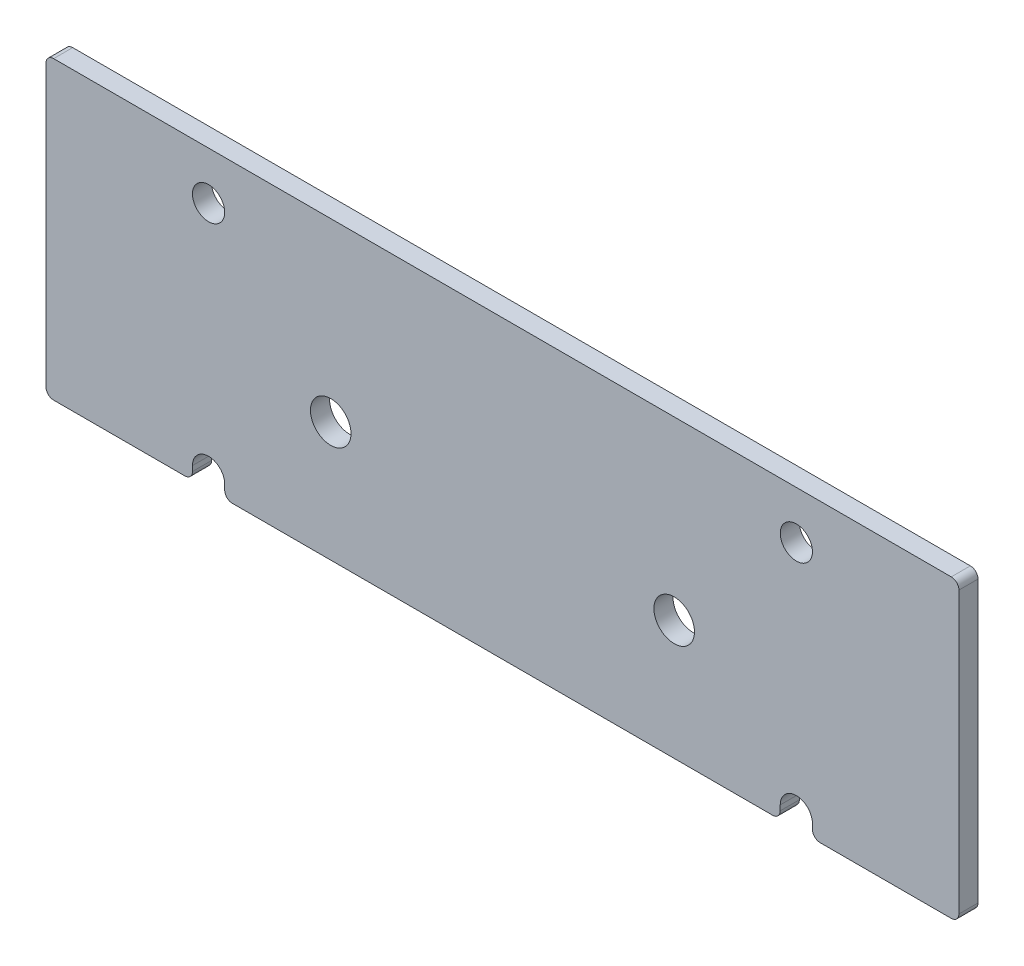
SolidWorks part; units mm, degrees
material "Plain Carbon Steel"
ref_plane "Front Plane" through (0, 0, 0) normal (0, 0, 1) x (1, 0, 0)
ref_plane "Top Plane" through (0, 0, 0) normal (0, 1, 0) x (1, 0, 0)
ref_plane "Right Plane" through (0, 0, 0) normal (1, 0, 0) x (0, 0, -1)
sketch "Sketch1" plane through (0, 0, 0) normal (0, 0, 1) x (1, 0, 0)
  line L0 (127, 0) -> (-127, 0) construction
  line L1 (101.6, -357.1875) -> (101.6, 357.1875) construction
  line L2 (152.4, 0) -> (152.4, 357.1875) construction
  line L3 (-101.6, -357.1875) -> (-101.6, 357.1875) construction
  line L4 (-152.4, -357.1875) -> (-152.4, 357.1875) construction
  line L5 (101.6, 59.0332) -> (-101.6, 262.2332) construction
  line L6 (101.6, 94.9543) -> (-101.6, 298.1543) construction
  line L7 (0, 196.5543) -> (0, 160.6332) construction
  line L8 (0, 178.5938) -> (152.4, 178.5938) construction
  line L9 (105.003, 12.7) -> (-105.003, 12.7) construction
  line L10 (105.003, -12.7) -> (-105.003, -12.7) construction
  line L11 (-101.6, 59.0332) -> (101.6, 262.2332) construction
  line L12 (-101.6, 94.9543) -> (101.6, 298.1543) construction
  line L13 (152.4, 0) -> (152.4, -357.1875) construction
  line L14 (-101.6, -94.9543) -> (101.6, -298.1543) construction
  line L15 (-101.6, -59.0332) -> (101.6, -262.2332) construction
  line L16 (101.6, -94.9543) -> (-101.6, -298.1543) construction
  line L17 (101.6, -59.0332) -> (-101.6, -262.2332) construction
  line L18 (-179.07, -25.4) -> (-179.07, 128.4583)
  line L19 (-179.07, 128.4583) -> (179.07, 128.4583)
  line L20 (179.07, 128.4583) -> (179.07, -25.4)
  line L21 (179.07, -25.4) -> (153.67, -25.4)
  line L22 (153.67, -25.4) -> (153.67, -1.27)
  line L23 (100.33, -1.27) -> (100.33, -25.4)
  line L24 (100.33, -25.4) -> (-100.33, -25.4)
  line L25 (-100.33, -25.4) -> (-100.33, -1.27)
  line L26 (-153.67, -1.27) -> (-153.67, -25.4)
  line L27 (-179.07, -25.4) -> (-153.67, -25.4)
  circle A0 centre (-127, 0) radius 25.4 construction
  circle A1 centre (127, 0) radius 25.4 construction
  circle A2 centre (-127, 357.1875) radius 25.4 construction
  circle A3 centre (127, 357.1875) radius 25.4 construction
  arc A4 (100.33, -1.27) -> (153.67, -1.27) centre (127, -1.27) cw
  arc A5 (-100.33, -1.27) -> (-153.67, -1.27) centre (-127, -1.27) ccw
  circle A6 centre (96.139, 108.1383) radius 5.461 construction
  point P23 (0, 178.5938)
  point P33 (101.6, 0)
  point P37 (-152.4, 0)
  point P38 (-101.6, 0)
  point P53 (127, 25.4)
  point P54 (127, 25.4)
  dimension "D2" = 50.8
  dimension "D7" = 26.67
  dimension "D9" = 25.4
  dimension "D10" = 10.922
  dimension "D1" = 254
  dimension "D3" = 357.1875
  dimension "D4" = 25.4
  dimension "D5" = 45
  dimension "D6" = 25.4
  dimension "D8" = 25.4
  dimension "D11" = 20.32
extrude "Boss-Extrude1" add sketch "Sketch1" along normal blind 6.35
sketch "Sketch9" plane through (0, 0, 6.35) normal (0, 0, 1) x (1, 0, 0)
  line L0 (-151.892, 128.4583) -> (-151.892, 8.3048)
  line L2 (-152.4, -357.1875) -> (-152.4, 357.1875) construction
  line L3 (179.07, 128.4583) -> (-179.07, 128.4583) construction
  line L4 (-151.892, 128.4583) -> (-179.07, 128.4583)
  line L5 (-179.07, 128.4583) -> (-179.07, -25.4)
  line L6 (-179.07, -25.4) -> (-153.67, -25.4)
  line L7 (-179.07, -25.4) -> (-153.67, -25.4) construction
  line L8 (-153.67, -25.4) -> (-153.67, -1.27) construction
  line L9 (-153.67, -25.4) -> (-153.67, -1.27)
  line L10 (0, 0) -> (0, 128.4583) construction
  line L11 (153.67, -25.4) -> (153.67, -1.27)
  line L12 (179.07, -25.4) -> (153.67, -25.4)
  line L13 (179.07, 128.4583) -> (179.07, -25.4)
  line L14 (151.892, 128.4583) -> (179.07, 128.4583)
  line L15 (151.892, 128.4583) -> (151.892, 8.3048)
  arc A0 (-100.33, -1.27) -> (-153.67, -1.27) centre (-127, -1.27) ccw construction
  arc A1 (-153.67, -1.27) -> (-151.892, 8.3048) centre (-127, -1.27) cw
  arc A2 (153.67, -1.27) -> (151.892, 8.3048) centre (127, -1.27) ccw
  dimension "D1" = 0.508
extrude "Cut-Extrude3" cut sketch "Sketch9" against normal through all
hole_wizard "27/64 (0.42188) Diameter Hole1" positions "Sketch2" profile "Sketch3" hole size "27/64" standard "ANSI Inch" end condition through all
sketch "Sketch2" plane through (0, 0, 6.35) normal (0, 0, 1) x (1, 0, 0)
  line L0 (-127, 0) -> (-127, 128.4583) construction
  line L1 (-179.07, 128.4583) -> (179.07, 128.4583) construction
  line L2 (0, 128.4583) -> (0, -25.4) construction
  line L3 (100.33, -25.4) -> (-100.33, -25.4) construction
  line L4 (-101.6, -357.1875) -> (-101.6, 357.1875) construction
  line L5 (151.892, 128.4583) -> (-151.892, 128.4583) construction
  point P0 (-97.79, 34.29)
  point P2 (-97.79, 112.5833)
  point P19 (97.79, 34.29)
  point P22 (97.79, 112.5833)
  dimension "D1" = 15.875
  dimension "D2" = 3.81
  dimension "D3" = 34.29
sketch "Sketch3" plane through (-97.79, 34.29, 6.35) normal (1, 0, 0) x (0, -1, 0)
  line L0 (0, 0) -> (0, 6.35)
  line L1 (0, 6.35) -> (5.3579, 6.35)
  line L2 (5.3579, 6.35) -> (5.3579, 0)
  line L5 (5.3579, 0) -> (0, 0)
  line L11 (0, -6.35) -> (0, 107.95) construction
  dimension "Thru Hole Dia." = 10.7158
  dimension "Thru Hole Depth" = 6.35
fillet "Fillet1" radius 2.54 6 edges at (100.33, -25.4, 3.175) (-100.33, -25.4, 3.175) (151.892, 8.3048, 3.175) (151.892, 128.4583, 3.175) (-151.892, 128.4583, 3.175) (-151.892, 8.3048, 3.175)
hole_wizard "1/2 Clearance Hole1" positions "Sketch4" profile "Sketch5" hole size "1/2" standard "ANSI Inch" end condition through all
sketch "Sketch4" plane through (0, 0, 6.35) normal (0, 0, 1) x (1, 0, 0)
  line L1 (0, 0) -> (0, 160.6332) construction
  line L2 (127, 0) -> (-127, 0) construction
  line L4 (105.003, 12.7) -> (-105.003, 12.7) construction
  line L5 (101.6, -357.1875) -> (101.6, 357.1875) construction
  circle A0 centre (57.15, 69.85) radius 12.7 construction
  point P0 (57.15, 69.85)
  point P18 (-57.15, 69.85)
  dimension "D1" = 25.4
  dimension "D2" = 57.15
  dimension "D3" = 44.45
sketch "Sketch5" plane through (57.15, 69.85, 6.35) normal (1, 0, 0) x (0, -1, 0)
  line L0 (0, 0) -> (0, 6.35)
  line L1 (0, 6.35) -> (6.7462, 6.35)
  line L2 (6.7462, 6.35) -> (6.7462, 0)
  line L5 (6.7462, 0) -> (0, 0)
  line L11 (0, -6.35) -> (0, 107.95) construction
  dimension "Thru Hole Dia." = 13.4925
  dimension "Thru Hole Depth" = 6.35
sketch "Sketch6" plane through (0, 0, 6.35) normal (0, 0, 1) x (1, 0, 0)
  line L0 (-117.8622, 128.4583) -> (-117.8622, 23.7857) construction
  line L1 (149.352, 128.4583) -> (-149.352, 128.4583) construction
  arc A0 (-100.33, -1.27) -> (-147.4083, 15.8994) centre (-127, -1.27) ccw construction
ref_plane "Plane1" through (-117.8622, 0, 0) normal (1, 0, 0) x (0, 0, -1)
sketch "Sketch7" plane through (0, 0, 6.35) normal (0, 0, 1) x (1, 0, 0)
  line L0 (-151.892, 30.0333) -> (151.892, 30.0333)
  line L3 (-151.892, 30.0333) -> (-151.892, -25.4)
  line L4 (-151.892, -25.4) -> (151.892, -25.4)
  line L5 (151.892, -25.4) -> (151.892, 30.0333)
  line L6 (-97.79, -25.4) -> (97.79, -25.4) construction
  line L7 (149.352, 128.4583) -> (-149.352, 128.4583) construction
  line L8 (-151.892, 17.5346) -> (-151.892, 125.9183) construction
  line L9 (151.892, 125.9183) -> (151.892, 17.5346) construction
  dimension "D1" = 98.425
extrude "Cut-Extrude1" cut sketch "Sketch7" against normal through all
sketch "Sketch8" plane through (0, 0, 6.35) normal (0, 0, 1) x (1, 0, 0)
  line L4 (-101.0438, 30.0333) -> (-151.892, 30.0333) construction
  line L8 (-126.4679, 30.0333) -> (-126.4679, 128.4583) construction
  line L9 (-101.0438, 30.0333) -> (-151.892, 30.0333) construction
  line L10 (149.352, 128.4583) -> (-149.352, 128.4583) construction
  line L11 (-94.5362, 30.0333) -> (-92.4321, 30.0333)
  line L12 (-92.4321, 34.29) -> (-94.5362, 30.0333)
  line L13 (-92.4321, 34.29) -> (-92.4321, 30.0333)
  line L14 (-103.1479, 34.29) -> (-103.1479, 30.0333)
  line L15 (-103.1479, 34.29) -> (-101.0438, 30.0333)
  line L16 (-101.0438, 30.0333) -> (-103.1479, 30.0333)
  line L17 (0, 30.0333) -> (0, 128.4583) construction
  line L18 (94.5362, 30.0333) -> (-94.5362, 30.0333) construction
  line L25 (101.0438, 30.0333) -> (103.1479, 30.0333)
  line L26 (103.1479, 34.29) -> (101.0438, 30.0333)
  line L27 (103.1479, 34.29) -> (103.1479, 30.0333)
  line L28 (92.4321, 34.29) -> (92.4321, 30.0333)
  line L29 (92.4321, 34.29) -> (94.5362, 30.0333)
  line L30 (94.5362, 30.0333) -> (92.4321, 30.0333)
  line L31 (-97.79, 34.29) -> (-97.79, 39.6479) construction
  arc A1 (-94.5362, 30.0333) -> (-101.0438, 30.0333) centre (-97.79, 34.29) ccw construction
  arc A2 (-94.5362, 30.0333) -> (-101.0438, 30.0333) centre (-97.79, 34.29) ccw construction
extrude "Cut-Extrude2" cut sketch "Sketch8" against normal through all
fillet "Fillet2" radius 2.54 6 edges at (-103.1479, 30.0333, 3.175) (-92.4321, 30.0333, 3.175) (92.4321, 30.0333, 3.175) (103.1479, 30.0333, 3.175) (151.892, 30.0333, 3.175) (-151.892, 30.0333, 3.175)
